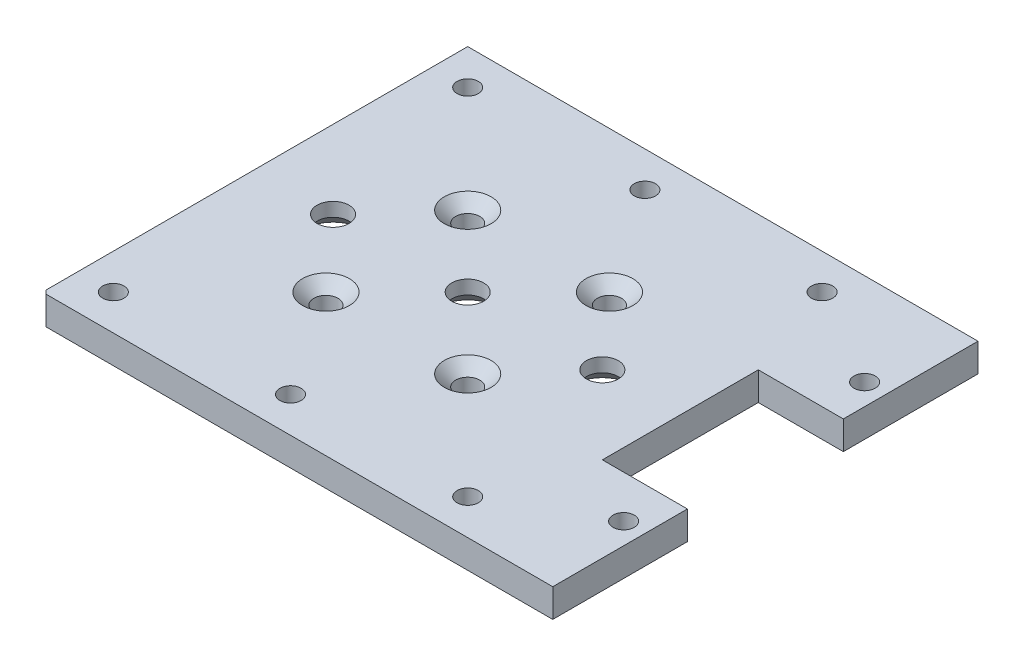
SolidWorks part; units mm, degrees
ref_plane "前视基准面" through (0, 0, 0) normal (0, 0, 1) x (1, 0, 0)
ref_plane "上视基准面" through (0, 0, 0) normal (0, 1, 0) x (1, 0, 0)
ref_plane "右视基准面" through (0, 0, 0) normal (1, 0, 0) x (0, 0, -1)
other "Configuration Table"
sketch "草图1" plane through (0, 0, 0) normal (0, 1, 0) x (1, 0, 0)
  line L1 (-30, -30) -> (30, -30)
  line L2 (-30, -30) -> (-30, 30)
  line L3 (-30, 30) -> (30, 30)
  line L4 (30, -30) -> (30, 30)
  line L5 (-30, -30) -> (30, 30) construction
  line L6 (-30, 30) -> (30, -30) construction
  point P0 (0, 0)
  dimension "D1" = 60
  dimension "D2" = 60
extrude "凸台-拉伸1" add sketch "草图1" along normal blind 4
hole_wizard "M3 十字槽沉头木螺钉的锥形沉头孔1" positions "草图2" profile "草图3" countersink size "M3" standard "GB" end condition through all
sketch "草图2" plane through (0, 4, 0) normal (0, 1, 0) x (1, 0, 0)
  point P6 (-10, 10)
  point P38 (10, 10)
  point P39 (10, -10)
  point P40 (-10, -10)
  dimension "D1" = 10
  dimension "D2" = 10
  dimension "D3" = 4
sketch "草图3" plane through (-10, 4, -10) normal (1, 0, 0) x (0, 0, 1)
  line L0 (0, 0) -> (0, 4)
  line L1 (0, 4) -> (1.7, 4)
  line L2 (1.7, 4) -> (1.7, 1.6)
  line L3 (1.7, 1.6) -> (3.3, 0)
  line L5 (3.3, 0) -> (0, 0)
  line L6 (-1.7, 1.6) -> (-3.3, 0) construction
  line L11 (0, -6.35) -> (0, 107.95) construction
  dimension "通孔孔直径" = 3.4
  dimension "通孔孔深度" = 4
  dimension "近端锥形沉头孔直径" = 6.6
  dimension "近端锥形沉头孔角度" = 90
hole_wizard "M4 十字槽沉头木螺钉的锥形沉头孔1" positions "草图4" profile "草图5" countersink size "M4" standard "GB" end condition through all
sketch "草图4" plane through (0, 0, 0) normal (0, -1, 0) x (-1, 0, 0)
  line L0 (-30, 0) -> (30, 0) construction
  line L1 (-30, -30) -> (-30, 30) construction
  line L2 (30, 30) -> (30, -30) construction
  point P0 (19, 0)
  point P2 (0, 0)
  point P4 (-19, 0)
  dimension "D1" = 19
  dimension "D2" = 19
sketch "草图5" plane through (-19, 0, 0) normal (1, 0, 0) x (0, 0, -1)
  line L0 (0, 0) -> (0, 4)
  line L1 (0, 4) -> (2.25, 4)
  line L2 (2.25, 4) -> (2.25, 2.05)
  line L3 (2.25, 2.05) -> (4.3, 0)
  line L5 (4.3, 0) -> (0, 0)
  line L6 (-2.25, 2.05) -> (-4.3, 0) construction
  line L11 (0, -6.35) -> (0, 107.95) construction
  dimension "通孔孔直径" = 4.5
  dimension "通孔孔深度" = 4
  dimension "近端锥形沉头孔直径" = 8.6
  dimension "近端锥形沉头孔角度" = 90
hole_wizard "孔1" positions "草图6" profile "草图7" legacy end condition through all
sketch "草图6" plane through (0, 4, 0) normal (0, 1, 0) x (1, 0, 0)
  line L0 (30, 30) -> (-30, 30) construction
  line L1 (-30, 30) -> (-30, -30) construction
  line L3 (-30, -30) -> (30, -30) construction
  line L5 (0, -30) -> (0, 30) construction
  line L7 (30, -30) -> (30, 30) construction
  point P0 (25, 25)
  point P2 (25, -25)
  point P4 (0, -25)
  point P6 (-25, -25)
  point P8 (-25, 25)
  point P12 (0, 25)
  point P51 (0, 0)
  dimension "D1" = 5
  dimension "D2" = 5
  dimension "D3" = 5
  dimension "D4" = 5
  dimension "D5" = 5
  dimension "D6" = 5
  dimension "D7" = 5
  dimension "D8" = 5
  dimension "D9" = 5
  dimension "D10" = 5
sketch "草图7" plane through (25, 4, -25) normal (1, 0, 0) x (0, 0, 1)
  line L0 (0, 0) -> (0, 4)
  line L1 (0, 4) -> (1.5, 4)
  line L2 (1.5, 4) -> (1.5, 0)
  line L3 (1.5, 0) -> (0, 0)
  line L4 (0, 110) -> (0, -10) construction
  dimension "直径" = 3
  dimension "深度" = 4
sketch "草图9" plane through (0, 4, 0) normal (0, 1, 0) x (1, 0, 0)
  line L1 (30, -30) -> (42, -30)
  line L2 (30, -30) -> (30, -11)
  line L3 (30, -11) -> (42, -11)
  line L4 (42, -30) -> (42, -11)
  circle A0 centre (39, -17) radius 1.5
  dimension "D3" = 3
  dimension "D1" = 19
  dimension "D2" = 12
  dimension "D4" = 13
  dimension "D5" = 3
extrude "凸台-拉伸3" add sketch "草图9" against normal up to surface (4 mm away) up to face at (25, 0, -23.5)
chamfer "倒角1" distance 0.5 angle 45 1 edges at (-30, 2, 30)
ref_plane "基准面2" through (0, 0, 0) normal (0, 0, 1) x (1, 0, 0)
mirror "镜向1" about plane through (0, 0, 0) normal (0, 0, 1) of "凸台-拉伸3"
